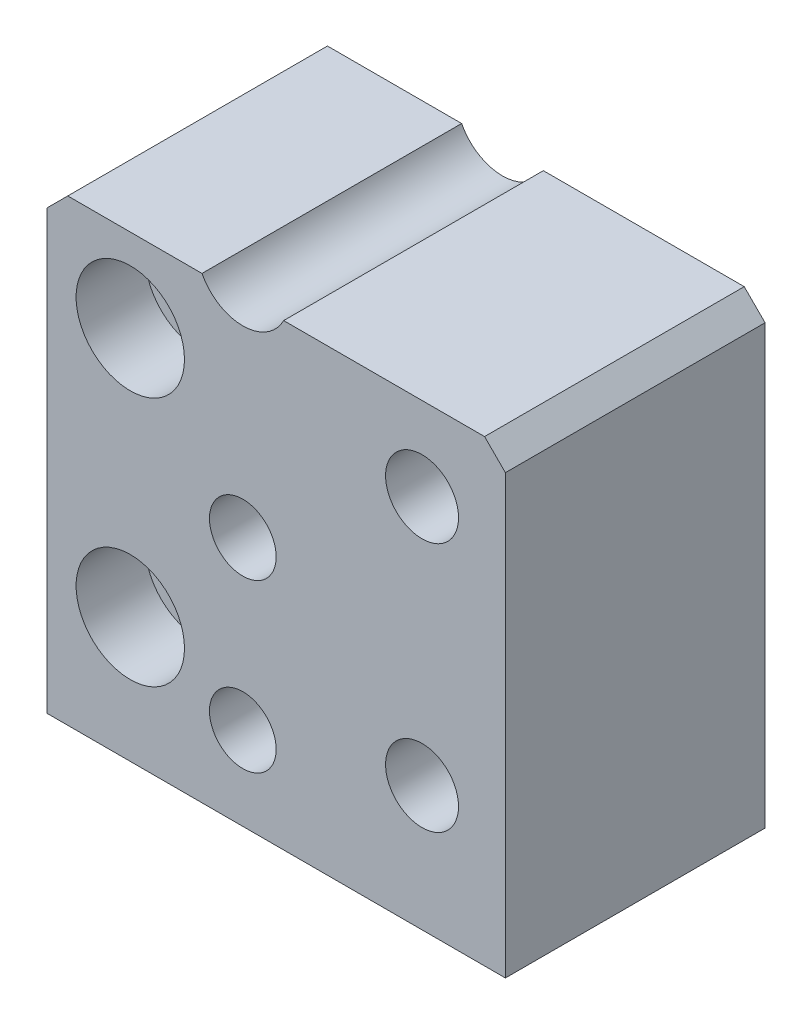
SolidWorks part; units mm, degrees
material "1.4301 (X5CrNi18-10)"
ref_plane "Vorne" through (0, 0, 0) normal (0, 0, 1) x (1, 0, 0)
ref_plane "Oben" through (0, 0, 0) normal (0, 1, 0) x (1, 0, 0)
ref_plane "Rechts" through (0, 0, 0) normal (1, 0, 0) x (0, 0, -1)
sketch "Skizze1" plane through (0, 0, 0) normal (0, 1, 0) x (1, 0, 0)
  line L1 (-55, 31.15) -> (55, 31.15)
  line L2 (-55, 31.15) -> (-55, -31.15)
  line L3 (-55, -31.15) -> (55, -31.15)
  line L4 (55, 31.15) -> (55, -31.15)
  line L5 (-55, 31.15) -> (55, -31.15) construction
  line L6 (-55, -31.15) -> (55, 31.15) construction
  point P0 (0, 0)
  dimension "D1" = 110
  dimension "D2" = 62.3
extrude "Aufsatz-Linear austragen1" add sketch "Skizze1" along normal blind 110
hole_wizard "Durchgangsloch für M161" positions "Skizze3" profile "Skizze2" hole size "M16" standard "Gabler-Normteile" end condition through all
sketch "Skizze3" plane through (0, 0, 31.15) normal (0, 0, 1) x (1, 0, 0)
  line L0 (-55, 0) -> (55, 0) construction
  line L2 (55, 110) -> (55, 0) construction
  point P0 (35, 90)
  point P2 (35, 30)
  dimension "D1" = 30
  dimension "D2" = 90
  dimension "D3" = 20
sketch "Skizze2" plane through (35, 90, 31.15) normal (1, 0, 0) x (0, -1, 0)
  line L0 (0, 0) -> (0, 62.3)
  line L1 (0, 62.3) -> (8.75, 62.3)
  line L2 (8.75, 62.3) -> (8.75, 0)
  line L5 (8.75, 0) -> (0, 0)
  line L11 (0, -6.35) -> (0, 107.95) construction
  dimension "Bohrerdurchmesser" = 17.5
  dimension "Bohrungstiefe" = 62.3
hole_wizard "Stirnsenkung für M16 Zylinderschraube mit Innensechskant1" positions "Skizze5" profile "Skizze4" counterbore size "M16" standard "Gabler-Normteile" end condition through all
sketch "Skizze5" plane through (0, 0, 31.15) normal (0, 0, 1) x (1, 0, 0)
  line L0 (-55, 0) -> (55, 0) construction
  line L2 (-55, 110) -> (-55, 0) construction
  point P0 (-35, 90)
  point P2 (-35, 30)
  dimension "D1" = 30
  dimension "D2" = 90
  dimension "D3" = 20
sketch "Skizze4" plane through (-35, 90, 31.15) normal (1, 0, 0) x (0, -1, 0)
  line L0 (0, 0) -> (0, 62.3)
  line L1 (0, 62.3) -> (8.75, 62.3)
  line L3 (8.75, 62.3) -> (8.75, 16.6)
  line L4 (8.75, 16.6) -> (13, 16.6)
  line L5 (13, 16.6) -> (13, 0)
  line L7 (13, 0) -> (0, 0)
  line L11 (0, -6.35) -> (0, 107.95) construction
  dimension "Bohrerdurchmesser" = 17.5
  dimension "Bohrungstiefe" = 62.3
  dimension "Senkdurchmesser2" = 26
  dimension "Senktiefe2" = 16.6
hole_wizard "Ø16.0 H7 (16) Durchmesser Bohrung2" positions "Skizze7" profile "Skizze6" hole size "Ø16.0" standard "Gabler-Normteile" end condition through all
sketch "Skizze7" plane through (0, 0, -31.15) normal (0, 0, -1) x (-1, 0, 0)
  line L2 (-55, 0) -> (55, 0) construction
  circle A0 centre (35, 90) radius 8.75 construction
  point P0 (8, 60)
  point P12 (8, 20)
  dimension "D1" = 60
  dimension "D2" = 27
  dimension "D3" = 20
sketch "Skizze6" plane through (-8, 60, -31.15) normal (1, 0, 0) x (0, 1, 0)
  line L0 (0, 0) -> (0, 62.3)
  line L1 (0, 62.3) -> (8, 62.3)
  line L2 (8, 62.3) -> (8, 0)
  line L5 (8, 0) -> (0, 0)
  line L11 (0, -6.35) -> (0, 107.95) construction
  dimension "Bohrerdurchmesser" = 16
  dimension "Bohrungstiefe" = 62.3
hole_wizard "Ø22.0 (22) Durchmesser Bohrung1" positions "Skizze13" profile "Skizze12" hole size "Ø22.0" standard "Gabler-Normteile" end condition through all
sketch "Skizze13" plane through (0, 0, -31.15) normal (0, 0, -1) x (-1, 0, 0)
  line L0 (-55, 0) -> (55, 0) construction
  line L1 (8, 60) -> (8, 115) construction
  point P0 (8, 115)
  dimension "D1" = 115
sketch "Skizze12" plane through (-8, 115, -31.15) normal (1, 0, 0) x (0, 1, 0)
  line L0 (0, 0) -> (0, 62.3)
  line L1 (0, 62.3) -> (11, 62.3)
  line L2 (11, 62.3) -> (11, 0)
  line L5 (11, 0) -> (0, 0)
  line L11 (0, -6.35) -> (0, 107.95) construction
  dimension "Bohrerdurchmesser" = 11
  dimension "Bohrungstiefe" = 62.3
chamfer "Fase1" distance 5 angle 45 2 edges at (-55, 110, 0) (55, 110, 0)
hole_wizard "Stirnsenkung für M16 Zylinderschraube mit Innensechskant2" positions "Skizze15" profile "Skizze14" counterbore size "M16" standard "Gabler-Normteile" end condition through all
sketch "Skizze15" plane through (0, 0, -31.15) normal (0, 0, -1) x (-1, 0, 0)
  point P0 (35, 90)
  point P3 (35, 30)
sketch "Skizze14" plane through (-35, 90, -31.15) normal (1, 0, 0) x (0, 1, 0)
  line L0 (0, 0) -> (0, 62.3)
  line L1 (0, 62.3) -> (8.75, 62.3)
  line L3 (8.75, 62.3) -> (8.75, 16.6)
  line L4 (8.75, 16.6) -> (13, 16.6)
  line L5 (13, 16.6) -> (13, 0)
  line L7 (13, 0) -> (0, 0)
  line L11 (0, -6.35) -> (0, 107.95) construction
  dimension "Bohrerdurchmesser" = 17.5
  dimension "Bohrungstiefe" = 62.3
  dimension "Senkdurchmesser2" = 26
  dimension "Senktiefe2" = 16.6
